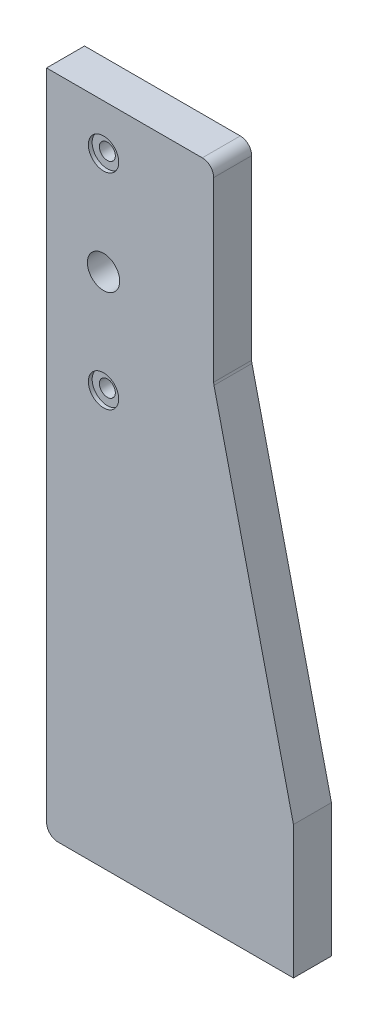
SolidWorks part; units mm, degrees
ref_plane "前视基准面" through (0, 0, 0) normal (0, 0, 1) x (1, 0, 0)
ref_plane "上视基准面" through (0, 0, 0) normal (0, 1, 0) x (1, 0, 0)
ref_plane "右视基准面" through (0, 0, 0) normal (1, 0, 0) x (0, 0, -1)
sketch "草图5" plane through (0, 0, 0) normal (0, 0, 1) x (1, 0, 0)
  line L0 (0, 0) -> (0, 175)
  line L1 (0, 175) -> (44, 175)
  line L2 (44, 175) -> (44, 125)
  line L3 (44, 125) -> (65, 35)
  line L4 (65, 35) -> (65, 0)
  line L5 (65, 0) -> (0, 0)
  line L6 (15, 175) -> (15, 0) construction
  dimension "D1" = 65
  dimension "D2" = 175
  dimension "D3" = 44
  dimension "D4" = 50
  dimension "D5" = 35
  dimension "D6" = 15
extrude "凸台-拉伸1" add sketch "草图5" along normal blind 10
sketch "草图6" plane through (0, 0, 10) normal (0, 0, 1) x (1, 0, 0)
  line L0 (15, 175) -> (15, 0) construction
  line L1 (44, 175) -> (0, 175) construction
  line L2 (0, 0) -> (65, 0) construction
  line L3 (0, 175) -> (0, 0) construction
  circle A0 centre (15, 163) radius 2.1
  circle A1 centre (15, 109) radius 2.1
  dimension "D2" = 4.2
  dimension "D3" = 12
  dimension "D4" = 54
  dimension "D1" = 15
extrude "切除-拉伸5" cut sketch "草图6" against normal through all contours A1 | A0
sketch "草图7" plane through (0, 0, 10) normal (0, 0, 1) x (1, 0, 0)
  circle A0 centre (15, 163) radius 4
  circle A1 centre (15, 109) radius 4
  dimension "D1" = 8
extrude "切除-拉伸6" cut sketch "草图7" against normal blind 1
fillet "圆角1" radius 3 3 edges at (0, 0, 5) (44, 125, 5) (44, 175, 5)
sketch "草图8" plane through (0, 0, 10) normal (0, 0, 1) x (1, 0, 0)
  line L0 (15, 163) -> (15, 109) construction
  circle A3 centre (15, 136) radius 4.25
  dimension "D1" = 8.5
extrude "切除-拉伸7" cut sketch "草图8" against normal blind 10
